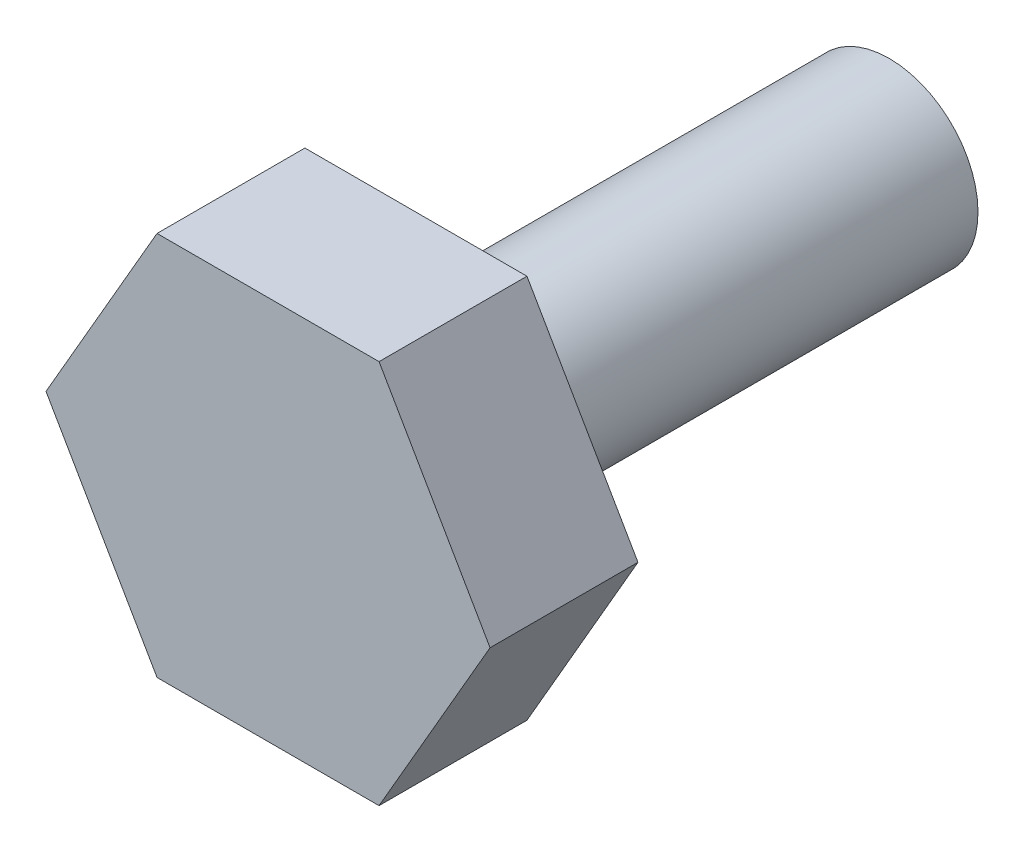
SolidWorks part; units mm, degrees
ref_plane "Front" through (0, 0, 0) normal (0, 0, 1) x (1, 0, 0)
ref_plane "Top" through (0, 0, 0) normal (0, 1, 0) x (1, 0, 0)
ref_plane "Right" through (0, 0, 0) normal (1, 0, 0) x (0, 0, -1)
sketch "Sketch1" plane through (0, 0, 0) normal (0, 0, 1) x (1, 0, 0)
  line L1 (4.766, -8.255) -> (9.5321, 0)
  line L2 (9.5321, 0) -> (4.766, 8.255)
  line L3 (4.766, 8.255) -> (-4.766, 8.255)
  line L4 (-4.766, 8.255) -> (-9.5321, 0)
  line L5 (-9.5321, 0) -> (-4.766, -8.255)
  line L6 (-4.766, -8.255) -> (4.766, -8.255)
  circle A0 centre (0, 0) radius 8.255 construction
  dimension "D1" = 16.51
extrude "Boss-Extrude1" add sketch "Sketch1" along normal blind 6.35
sketch "Sketch2" plane through (0, 0, 0) normal (0, 0, -1) x (-1, 0, 0)
  circle A0 centre (0, 0) radius 3.81
  dimension "D1" = 7.62
extrude "Boss-Extrude2" add sketch "Sketch2" along normal blind 20.32
